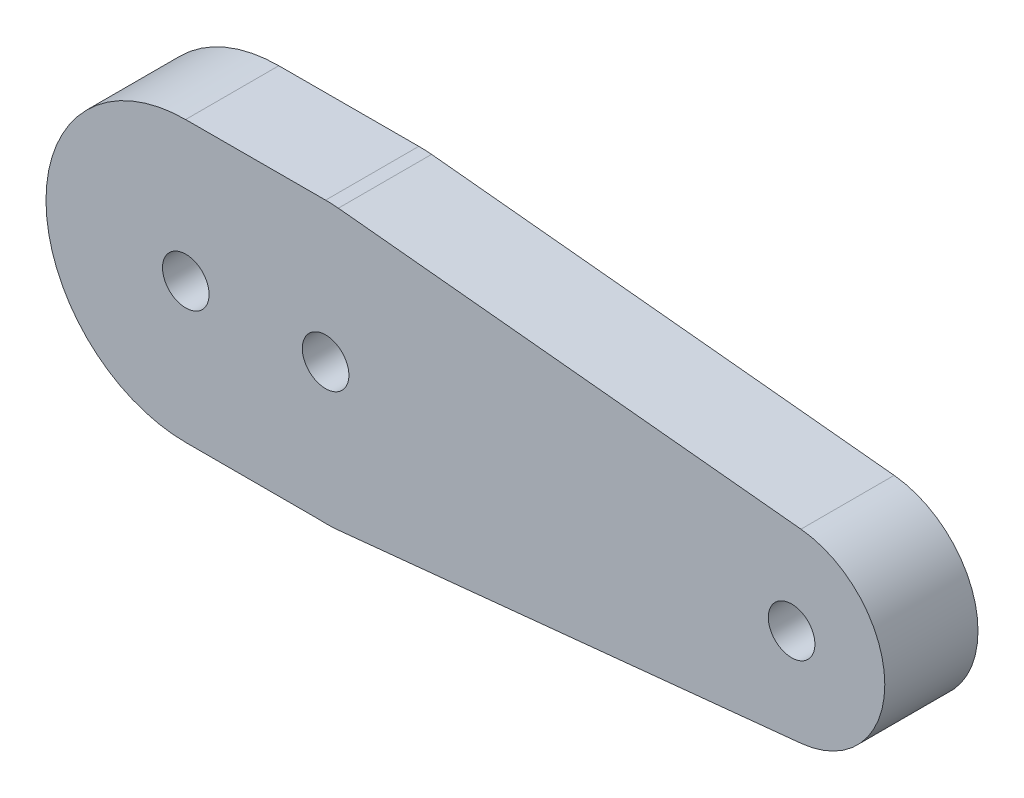
SolidWorks part; units mm, degrees
ref_plane "Front Plane" through (0, 0, 0) normal (0, 0, 1) x (1, 0, 0)
ref_plane "Top Plane" through (0, 0, 0) normal (0, 1, 0) x (1, 0, 0)
ref_plane "Right Plane" through (0, 0, 0) normal (1, 0, 0) x (0, 0, -1)
sketch "Sketch1" plane through (0, 0, 0) normal (0, 0, 1) x (1, 0, 0)
  line L0 (1.3706, 14.9583) -> (51.0041, 9.9495)
  line L1 (1.3706, -14.9583) -> (51.0041, -9.9495)
  line L2 (-15.0209, 15) -> (0, 15.021)
  line L3 (-15, -15) -> (-0.7932, -15)
  circle A0 centre (-15, 0) radius 2.5
  circle A1 centre (0, 0) radius 2.5
  circle A2 centre (50, 0) radius 2.5
  arc A4 (-15.0209, 15) -> (-15, -15) centre (-15, 0) ccw
  arc A5 (51.0041, -9.9495) -> (51.0041, 9.9495) centre (50, 0) ccw
  arc A6 (-0.7932, -15) -> (1.3706, -14.9583) centre (0, 0) ccw
  arc A7 (1.3706, 14.9583) -> (0, 15.021) centre (0, 0) ccw
  dimension "D1" = 20
  dimension "D2" = 15
  dimension "D4" = 5
  dimension "D5" = 5
  dimension "D3" = 50
  dimension "D6" = 15
extrude "Boss-Extrude1" add sketch "Sketch1" along normal mid plane 10
sketch "Sketch2" plane through (0, 0, 0) normal (0, 0, 1) x (1, 0, 0)
  line L0 (50, -1000) -> (50, 49000) construction
  line L1 (-15, -1000) -> (-15, 49000) construction
sketch "Sketch3" plane through (0, 0, 0) normal (0, 0, 1) x (1, 0, 0)
  line L0 (51.0041, 9.9495) -> (1.3706, 14.9583) construction
  line L1 (1.3706, -14.9583) -> (51.0041, -9.9495) construction
  line L2 (3.9499, 14.698) -> (3.9499, 23.599)
  line L3 (3.9499, 23.599) -> (-33.0984, 23.599)
  line L4 (-33.0984, 23.599) -> (-33.0984, -19.3341)
  line L5 (-33.0984, -19.3341) -> (3.0117, -19.3341)
  line L6 (3.0117, -19.3341) -> (3.0117, -14.7927)
  line L7 (22.5159, 8.3136) -> (31.4696, 5.9632)
  line L8 (31.4696, 5.9632) -> (38.1849, 2.7175)
  line L9 (28.289, -6.1533) -> (21.2552, 1.6112)
  line L10 (12.062, -6.1533) -> (16.0976, -3.4692)
  line L11 (18.2297, -3.4192) -> (21.9757, -7.1651)
  line L12 (13.422, -9.429) -> (20.8814, -8.4313)
  arc A0 (-9.9036, 9.6669) -> (-9.9036, -9.6669) centre (-15, 0) ccw
  arc A1 (18.2297, -3.4192) -> (16.0976, -3.4692) centre (17.2032, -5.1314) ccw
  arc A2 (20.8814, -8.4313) -> (21.9757, -7.1651) centre (21.1597, -7.5659) ccw
  spline S0 degree 3 poles (-9.9036, 9.6669) (-6.6521, 9.3201) (-2.5752, 12.1807) (1.7399, 14.763) (3.9499, 14.698) knots 0 0 0 0 0.582392 1 1 1 1
  spline S1 degree 3 poles (-9.9036, -9.6669) (-7.4765, -9.5332) (-5.1125, -11.3322) (-1.4199, -14.3078) (1.2483, -14.8931) (3.0117, -14.7927) knots 0 0 0 0 0.454121 0.625344 1 1 1 1
  spline S2 degree 3 poles (38.1849, 2.7175) (40.4644, 2.7256) (40.5673, -0.9319) (37.0228, -2.29) (33.1979, -3.7939) (30.5194, -5.9288) (28.289, -6.1533) knots 0 0 0 0 0.267175 0.422388 0.62445 1 1 1 1
  spline S3 degree 3 poles (21.729, 6.8238) (21.939, 7.3414) (22.4863, 7.3837) (22.5159, 8.3136) knots 0.760302 0.760302 0.760302 0.760302 1 1 1 1
  spline S4 degree 3 poles (21.2552, 1.6112) (18.0975, 5.3327) (21.5612, 3.1493) (21.729, 6.8238) knots 0 0 0 0 1 1 1 1
  spline S5 degree 3 poles (12.062, -6.1533) (11.8801, -6.849) (12.4954, -7.9277) (12.9664, -9.0639) (13.422, -9.429) knots 0 0 0 0 0.534202 1 1 1 1
